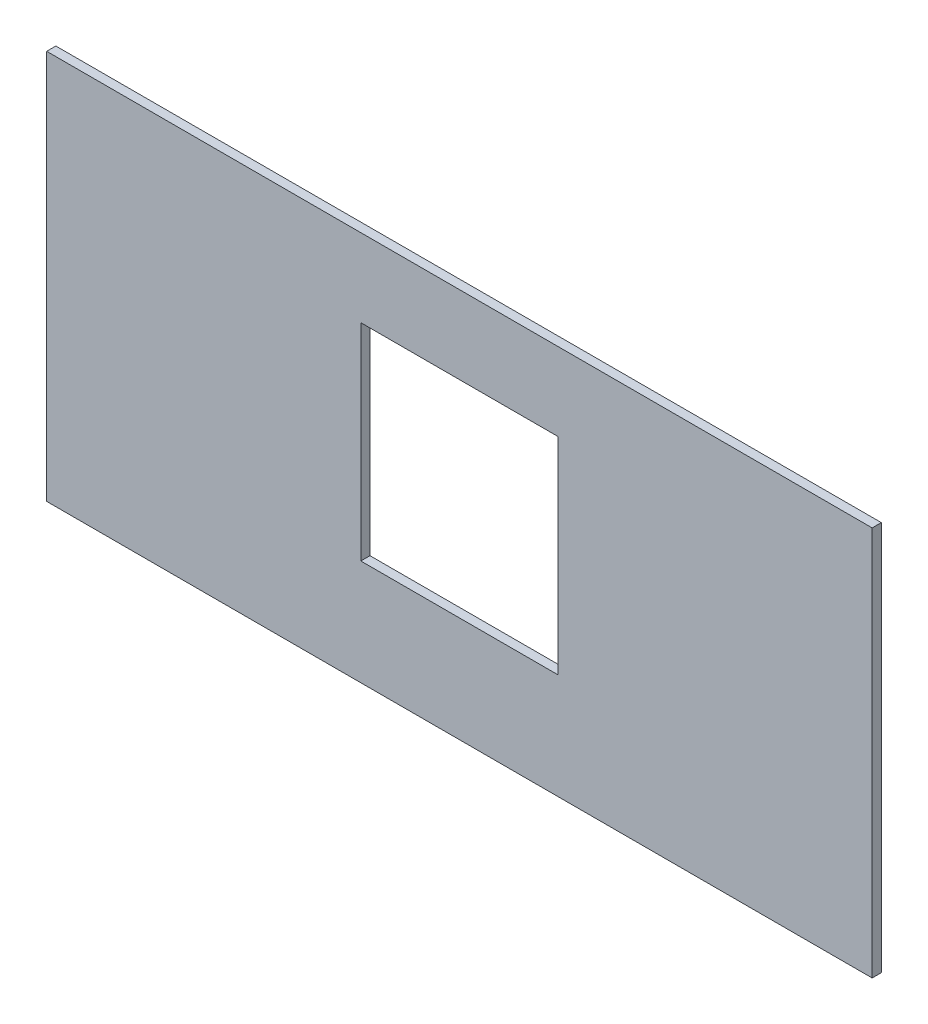
SolidWorks part; units mm, degrees
ref_plane "Front Plane" through (0, 0, 0) normal (0, 0, 1) x (1, 0, 0)
ref_plane "Top Plane" through (0, 0, 0) normal (0, 1, 0) x (1, 0, 0)
ref_plane "Right Plane" through (0, 0, 0) normal (1, 0, 0) x (0, 0, -1)
sketch "Sketch1" plane through (0, 0, 0) normal (0, 0, 1) x (1, 0, 0)
  line L1 (0, 0) -> (180, 0)
  line L2 (0, 0) -> (0, -85)
  line L3 (0, -85) -> (180, -85)
  line L4 (180, 0) -> (180, -85)
  dimension "D1" = 180
  dimension "D2" = 85
extrude "Boss-Extrude1" add sketch "Sketch1" along normal blind 2
sketch "Sketch2" plane through (0, 0, 2) normal (0, 0, 1) x (1, 0, 0)
  line L0 (180, 0) -> (0, 0) construction
  line L1 (68.5, -17) -> (111.5, -17)
  line L2 (68.5, -17) -> (68.5, -62)
  line L3 (68.5, -62) -> (111.5, -62)
  line L4 (111.5, -17) -> (111.5, -62)
  line L5 (180, -85) -> (180, 0) construction
  dimension "D1" = 45
  dimension "D2" = 43
  dimension "D3" = 17
  dimension "D4" = 68.5
extrude "Cut-Extrude1" cut sketch "Sketch2" against normal blind 50.8
